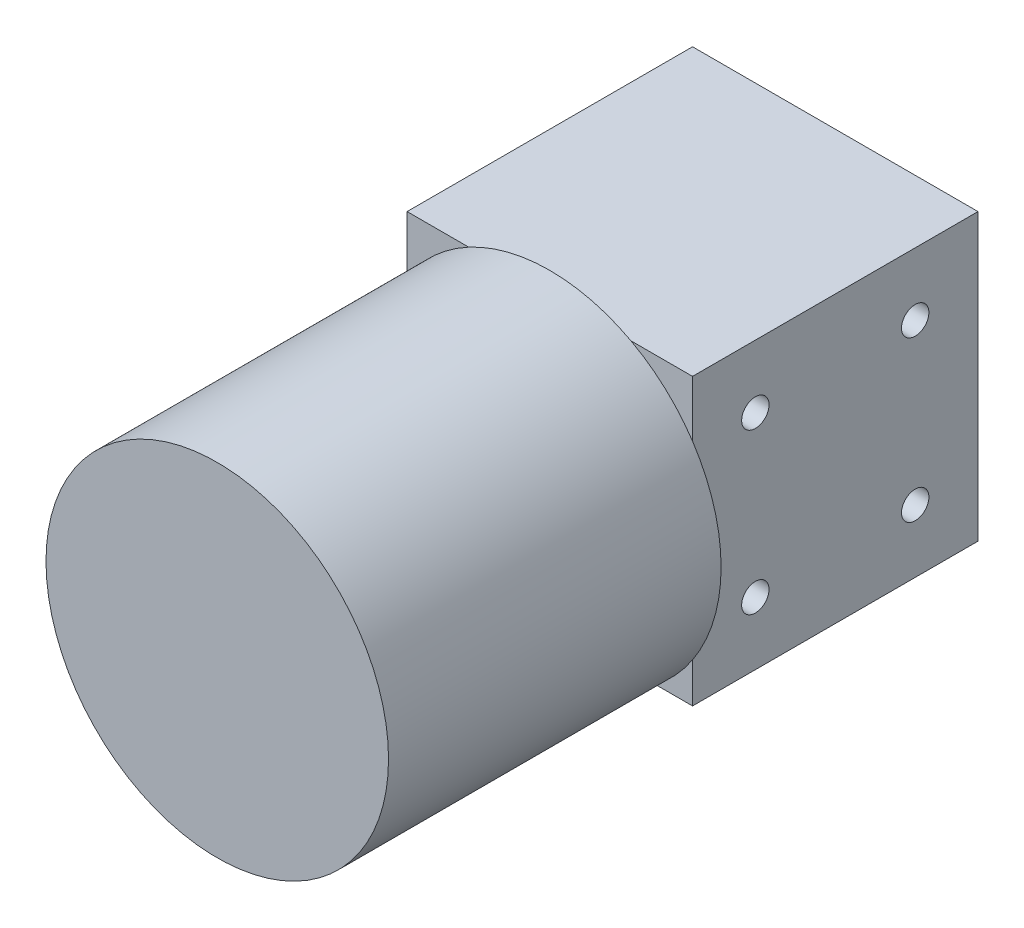
SolidWorks part; units mm, degrees
ref_plane "Front Plane" through (0, 0, 0) normal (0, 0, 1) x (1, 0, 0)
ref_plane "Top Plane" through (0, 0, 0) normal (0, 1, 0) x (1, 0, 0)
ref_plane "Right Plane" through (0, 0, 0) normal (1, 0, 0) x (0, 0, -1)
sketch "Sketch1" plane through (0, 0, 0) normal (0, 0, 1) x (1, 0, 0)
  line L0 (0, -23.5782) -> (50, -23.5782)
  line L1 (0, -23.5782) -> (0, 26.4218)
  line L2 (50, -23.5782) -> (50, 26.4218)
  line L3 (0, 26.4218) -> (50, 26.4218)
  dimension "D1" = 50
  dimension "D2" = 50
extrude "Boss-Extrude1" add sketch "Sketch1" along normal blind 50
sketch "Sketch2" plane through (0, 0, 50) normal (0, 0, 1) x (1, 0, 0)
  circle A0 centre (25, 0) radius 30
extrude "Boss-Extrude2" add sketch "Sketch2" along normal blind 58.25
sketch "Sketch3" plane through (0, 0, 0) normal (0, 0, -1) x (-1, 0, 0)
  circle A0 centre (-25, 0) radius 7.5
extrude "Cut-Extrude1" cut sketch "Sketch3" against normal blind 1
sketch "Sketch4" plane through (50, 0, 0) normal (1, 0, 0) x (0, 0, -1)
  line L0 (0, -23.5782) -> (0, 26.4218) construction
  line L1 (-50, 26.4218) -> (0, 26.4218) construction
  circle A0 centre (-39, 15.4218) radius 2.4
  circle A1 centre (-11, 15.4218) radius 2.4
  circle A2 centre (-11, -12.5782) radius 2.4
  circle A3 centre (-39, -12.5782) radius 2.4
  point P4 (0, 0)
  dimension "D1" = 2
  dimension "D3" = 11
  dimension "D4" = 11
  dimension "D2" = 2
extrude "Cut-Extrude2" cut sketch "Sketch4" against normal blind 15
sketch "Sketch5" plane through (0, 0, 0) normal (-1, 0, 0) x (0, 0, 1)
  line L0 (50, 26.4218) -> (0, 26.4218) construction
  line L1 (0, 26.4218) -> (0, -23.5782) construction
  circle A0 centre (11, 15.4218) radius 2.4
  circle A1 centre (39, 15.4218) radius 2.4
  circle A2 centre (39, -12.5782) radius 2.4
  circle A3 centre (11, -12.5782) radius 2.4
  dimension "D1" = 11
  dimension "D2" = 11
  dimension "D3" = 2
  dimension "D4" = 2
extrude "Cut-Extrude3" cut sketch "Sketch5" against normal blind 15
